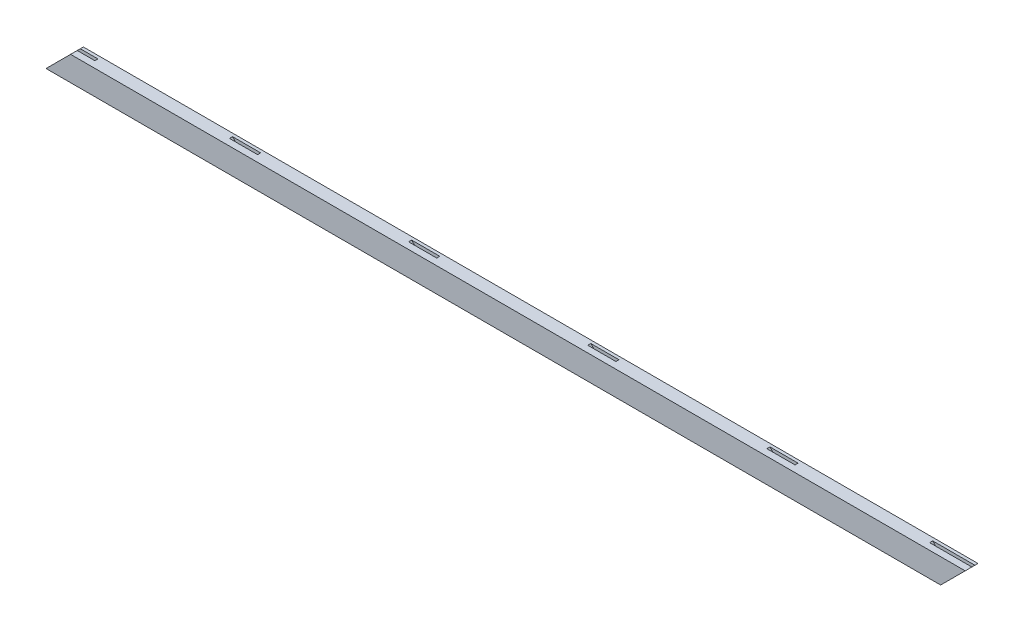
SolidWorks part; units mm, degrees
ref_plane "前视基准面" through (0, 0, 0) normal (0, 0, 1) x (1, 0, 0)
ref_plane "上视基准面" through (0, 0, 0) normal (0, 1, 0) x (1, 0, 0)
ref_plane "右视基准面" through (0, 0, 0) normal (1, 0, 0) x (0, 0, -1)
sketch "草图2" plane through (0, 0, 0) normal (0, 0, 1) x (1, 0, 0)
  line L0 (0, 0) -> (-48, -48)
  line L1 (-48, -48) -> (1700, -48)
  line L2 (1700, -48) -> (1748, 0)
  line L3 (1748, 0) -> (0, 0)
  dimension "D1" = 1748
  dimension "D2" = 45
  dimension "D3" = 45
  dimension "D4" = 48
extrude "凸台-拉伸1" add sketch "草图2" along normal blind 25
sketch "草图3" plane through (0, 0, 0) normal (0, 0, -1) x (-1, 0, 0)
  line L0 (-1402.5, 0) -> (-1395, -7.5)
  line L1 (-1748, 0) -> (0, 0) construction
  line L2 (-1395, -7.5) -> (-1355, -7.5)
  line L3 (-1355, -7.5) -> (-1347.5, 0)
  line L4 (-1402.5, 0) -> (-1347.5, 0)
  line L5 (-1700, -48) -> (-1748, 0) construction
  point P8 (-1724, -24)
  point P9 (-1375, -7.5)
  dimension "D1" = 7.5
  dimension "D2" = 45
  dimension "D3" = 45
  dimension "D4" = 40
  dimension "D5" = 349
extrude "切除-拉伸1" cut sketch "草图3" against normal blind 6 from offset 6 offset against normal yes
pattern_linear "阵列(线性)1" count 4 spacing 350 along (-1, 0, 0) of "切除-拉伸1"
ref_plane "基准面1" through (0, -24, 0) normal (0, 1, 0) x (1, 0, 0)
mirror "镜向1" about plane through (0, -24, 0) normal (0, 1, 0) of "阵列(线性)1", "切除-拉伸1"
sketch "草图4" plane through (0, 0, 25) normal (0, 0, 1) x (1, 0, 0)
  line L0 (1665.5, 0) -> (1673, -7.5)
  line L1 (1748, 0) -> (0, 0) construction
  line L2 (1673, -7.5) -> (1740.5, -7.5)
  line L3 (1700, -48) -> (1748, 0) construction
  line L4 (1740.5, -7.5) -> (1748, 0)
  line L5 (1748, 0) -> (1665.5, 0)
  line L6 (1665.5, -48) -> (1673, -40.5)
  line L7 (-48, -48) -> (1700, -48) construction
  line L8 (1673, -40.5) -> (1707.5, -40.5)
  line L9 (1707.5, -40.5) -> (1700, -48)
  line L10 (1700, -48) -> (1665.5, -48)
  line L11 (34.5, -48) -> (27, -40.5)
  line L12 (27, -40.5) -> (-40.5, -40.5)
  line L13 (0, 0) -> (-48, -48) construction
  line L14 (-40.5, -40.5) -> (-48, -48)
  line L15 (-48, -48) -> (34.5, -48)
  line L16 (34.5, 0) -> (27, -7.5)
  line L17 (27, -7.5) -> (-7.5, -7.5)
  line L18 (-7.5, -7.5) -> (0, 0)
  line L19 (0, 0) -> (34.5, 0)
  dimension "D1" = 7.5
  dimension "D2" = 75
  dimension "D3" = 27
  dimension "D4" = 7.5
  dimension "D5" = 7.5
  dimension "D6" = 7.5
  dimension "D7" = 27
  dimension "D8" = 75
extrude "切除-拉伸2" cut sketch "草图4" against normal blind 6 from offset 13
